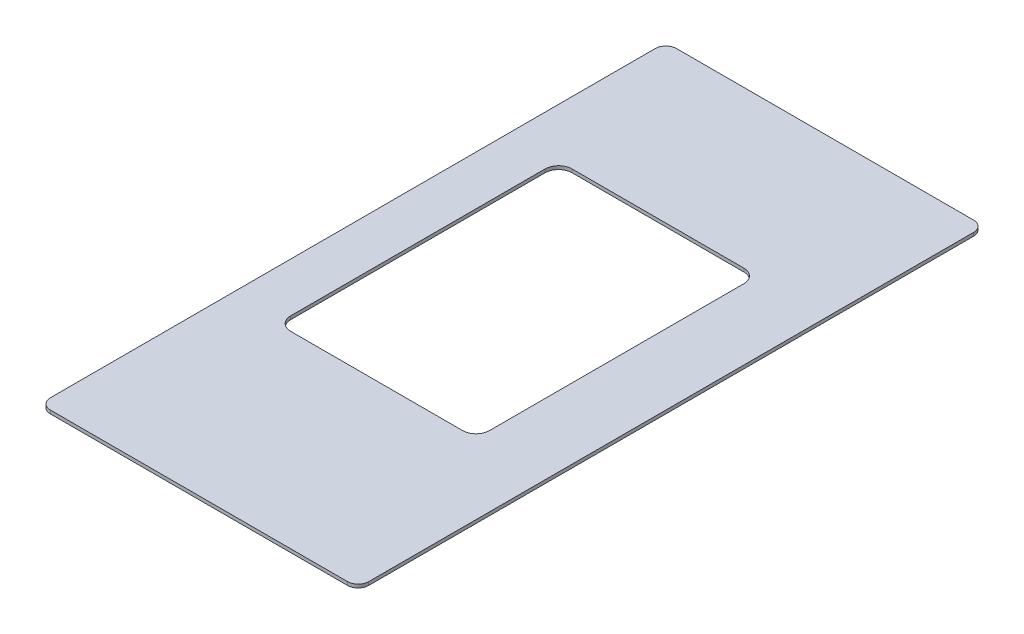
SolidWorks part; units mm, degrees
material "5052-H32"
ref_plane "Front Plane" through (0, 0, 0) normal (0, 0, 1) x (1, 0, 0)
ref_plane "Top Plane" through (0, 0, 0) normal (0, 1, 0) x (1, 0, 0)
ref_plane "Right Plane" through (0, 0, 0) normal (1, 0, 0) x (0, 0, -1)
sketch "Sketch9" plane through (0, 0, 0) normal (0, 1, 0) x (1, 0, 0)
  line L0 (-130, 0) -> (130, 0) construction
  line L1 (-130, 550) -> (130, 550) construction
  line L2 (-130, 550) -> (-130, 0) construction
  line L4 (130, 550) -> (130, 0) construction
  line L14 (83.6625, 157.4438) -> (-103.6625, 157.4438)
  line L15 (-150, 570) -> (150, 570)
  line L16 (150, 570) -> (150, -20)
  line L17 (-150, -20) -> (150, -20)
  line L18 (-150, 570) -> (-150, -20)
  line L19 (-10, 290) -> (155.5075, 290) construction
  line L20 (83.6625, 157.4438) -> (83.6625, 422.5563)
  line L21 (83.6625, 422.5563) -> (-103.6625, 422.5563)
  line L22 (-103.6625, 157.4438) -> (-103.6625, 422.5563)
  line L23 (83.6625, 157.4438) -> (-103.6625, 422.5563) construction
  line L24 (83.6625, 422.5563) -> (-103.6625, 157.4438) construction
  line L25 (-130, 0) -> (130, 0) construction
  point P5 (-10, 290)
  point P12 (-17.5676, 520)
  point P17 (-15.5075, 520)
  point P19 (0, 0)
  dimension "D10" = 550
  dimension "D9" = 260
  dimension "D3" = 265.1125
  dimension "D4" = 187.325
  dimension "D5" = 260
  dimension "D6" = 140
  dimension "D2" = 20
extrude "Boss-Extrude7" add sketch "Sketch9" along normal blind 3.175 separate body
fillet "Fillet4" radius 10 4 edges at (-150, 1.5875, -570) (150, 1.5875, -570) (-150, 1.5875, 20) (150, 1.5875, 20)
sketch "Sketch10" plane through (0, 0, 0) normal (0, 1, 0) x (1, 0, 0)
  line L0 (0, 0) -> (0, 500) construction
  line L1 (-130, 500) -> (130, 500) construction
  line L2 (-130, 500) -> (-130, 0) construction
  line L3 (-130, 0) -> (130, 0) construction
  line L4 (130, 500) -> (130, 0) construction
  line L8 (-150, 520) -> (-150, -20) construction
  line L9 (-150, -20) -> (150, -20) construction
  line L10 (150, 520) -> (150, -20) construction
  line L11 (-150, 520) -> (150, 520) construction
  line L15 (130, 250) -> (-130, 250) construction
  circle A0 centre (-140, -10) radius 2.5
  circle A2 centre (-140, 42) radius 2.5
  circle A3 centre (-140, 94) radius 2.5
  circle A4 centre (-140, 146) radius 2.5
  circle A5 centre (-140, 198) radius 2.5
  circle A6 centre (-140, 250) radius 2.5
  circle A7 centre (-140, 302) radius 2.5
  circle A8 centre (-140, 354) radius 2.5
  circle A9 centre (-140, 406) radius 2.5
  circle A10 centre (-140, 458) radius 2.5
  circle A16 centre (-140, 510) radius 2.5
  circle A17 centre (-83, 510) radius 2.5
  circle A18 centre (-26, 510) radius 2.5
  circle A19 centre (31, 510) radius 2.5
  circle A20 centre (88, 510) radius 2.5
  circle A21 centre (145, 510) radius 2.5
  circle A22 centre (145, 458) radius 2.5
  circle A23 centre (145, 406) radius 2.5
  circle A24 centre (145, 354) radius 2.5
  circle A25 centre (145, 302) radius 2.5
  circle A26 centre (145, 250) radius 2.5
  circle A27 centre (145, 198) radius 2.5
  circle A28 centre (145, 146) radius 2.5
  circle A29 centre (145, 94) radius 2.5
  circle A30 centre (145, 42) radius 2.5
  circle A31 centre (145, -10) radius 2.5
  circle A38 centre (89, -10) radius 2.5
  circle A39 centre (33, -10) radius 2.5
  circle A40 centre (-23, -10) radius 2.5
  circle A41 centre (-79, -10) radius 2.5
  dimension "D4" = 5
  dimension "D7" = 5
  dimension "D2" = 10
  dimension "D3" = 10
  dimension "D5" = 6
  dimension "D6" = 11
  dimension "D8" = 11
  dimension "D9" = 260
  dimension "D1" = 20
fillet "Fillet5" radius 12.7 4 edges at (-103.6625, 1.5875, -157.4438) (83.6625, 1.5875, -157.4438) (83.6625, 1.5875, -422.5563) (-103.6625, 1.5875, -422.5563)
extrude "Bolt Holes" [suppressed] cut sketch "Sketch10" along normal up to next
equation "\"W\"= 260"
equation "\"D9@Sketch9\"=\"W\""
equation "\"L\" = 550"
equation "\"D10@Sketch9\"=\"L\""
equation "\"Offset\"= 20"
equation "\"D2@Sketch9\"=\"Offset\""
equation "\"D5@Sketch9\"=\"L\"/2-15"
equation "\"D6@Sketch9\"=\"W\"/2+10"
